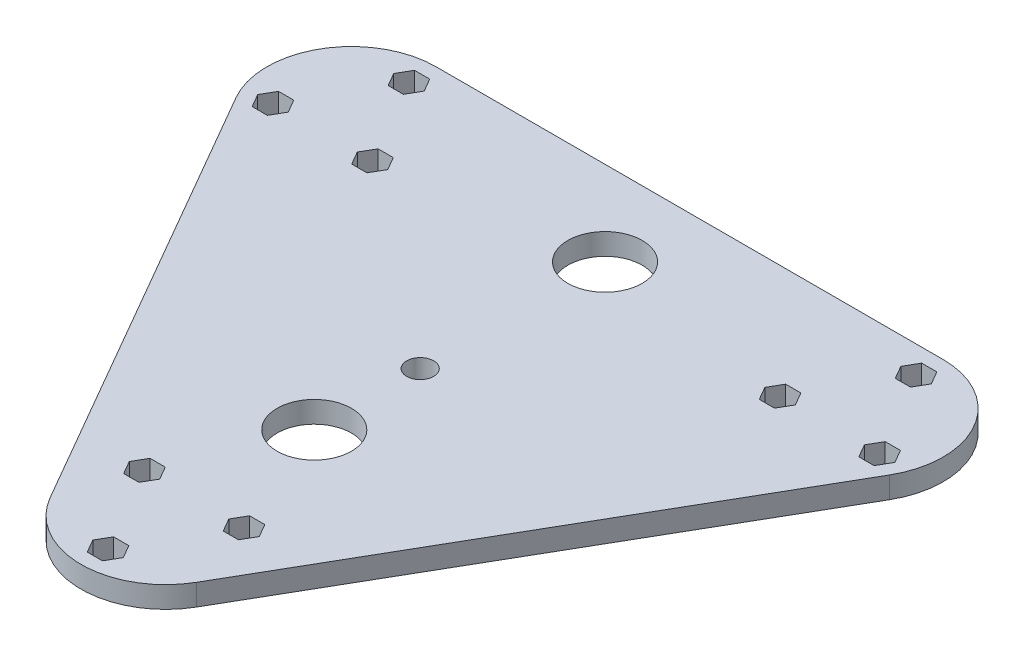
SolidWorks part; units mm, degrees
ref_plane "Plan de face" through (0, 0, 0) normal (0, 0, 1) x (1, 0, 0)
ref_plane "Plan de dessus" through (0, 0, 0) normal (0, 1, 0) x (1, 0, 0)
ref_plane "Plan de droite" through (0, 0, 0) normal (1, 0, 0) x (0, 0, -1)
sketch "Esquisse1" plane through (0, 0, 0) normal (0, 1, 0) x (1, 0, 0)
  line L0 (-96.6546, 52.5069) -> (-21.6546, -77.4931)
  line L1 (96.6546, 52.5069) -> (21.6546, -77.4931)
  line L2 (-75, 90) -> (75, 90)
  line L3 (-75, 65) -> (75, 65) construction
  arc A3 (-75, 90) -> (-96.6546, 52.5069) centre (-75, 65) ccw
  arc A4 (96.6546, 52.5069) -> (75, 90) centre (75, 65) ccw
  arc A5 (-21.6546, -77.4931) -> (21.6546, -77.4931) centre (0, -65) ccw
  circle A6 centre (0, 65) radius 11
  dimension "D1" = 22
  dimension "D6" = 50
  dimension "D2" = 65
  dimension "D3" = 65
  dimension "D4" = 150
  dimension "D5" = 75
extrude "Boss.-Extru.1" add sketch "Esquisse1" along normal blind 6.35
sketch "Esquisse3" plane through (0, 0, 0) normal (0, -1, 0) x (1, 0, 0)
  line L0 (75, -90) -> (-75, -90) construction
  line L1 (-79.5033, -82) -> (-77.2517, -85.9)
  line L2 (-77.2517, -85.9) -> (-72.7483, -85.9)
  line L3 (-72.7483, -85.9) -> (-70.4967, -82)
  line L4 (-70.4967, -82) -> (-72.7483, -78.1)
  line L5 (-72.7483, -78.1) -> (-77.2517, -78.1)
  line L6 (-77.2517, -78.1) -> (-79.5033, -82)
  line L7 (-94.2258, -56.5) -> (-91.9741, -60.4)
  line L8 (-91.9741, -60.4) -> (-87.4708, -60.4)
  line L9 (-87.4708, -60.4) -> (-85.2191, -56.5)
  line L10 (-85.2191, -56.5) -> (-87.4708, -52.6)
  line L11 (-87.4708, -52.6) -> (-91.9741, -52.6)
  line L12 (-91.9741, -52.6) -> (-94.2258, -56.5)
  line L13 (-64.7809, -56.5) -> (-62.5292, -60.4)
  line L14 (-62.5292, -60.4) -> (-58.0259, -60.4)
  line L15 (-58.0259, -60.4) -> (-55.7742, -56.5)
  line L16 (-55.7742, -56.5) -> (-58.0259, -52.6)
  line L17 (-58.0259, -52.6) -> (-62.5292, -52.6)
  line L18 (-62.5292, -52.6) -> (-64.7809, -56.5)
  line L19 (55.7757, -56.4992) -> (58.0274, -60.3992)
  line L20 (58.0274, -60.3992) -> (62.5307, -60.3992)
  line L21 (62.5307, -60.3992) -> (64.7824, -56.4992)
  line L22 (64.7824, -56.4992) -> (62.5307, -52.5992)
  line L23 (62.5307, -52.5992) -> (58.0274, -52.5992)
  line L24 (58.0274, -52.5992) -> (55.7757, -56.4992)
  line L25 (70.4981, -81.9992) -> (72.7498, -85.8992)
  line L26 (72.7498, -85.8992) -> (77.2531, -85.8992)
  line L27 (77.2531, -85.8992) -> (79.5048, -81.9992)
  line L28 (79.5048, -81.9992) -> (77.2531, -78.0992)
  line L29 (77.2531, -78.0992) -> (72.7498, -78.0992)
  line L30 (72.7498, -78.0992) -> (70.4981, -81.9992)
  line L31 (85.2206, -56.4992) -> (87.4722, -60.3992)
  line L32 (87.4722, -60.3992) -> (91.9756, -60.3992)
  line L33 (91.9756, -60.3992) -> (94.2272, -56.4992)
  line L34 (94.2272, -56.4992) -> (91.9756, -52.5992)
  line L35 (91.9756, -52.5992) -> (87.4722, -52.5992)
  line L36 (87.4722, -52.5992) -> (85.2206, -56.4992)
  line L37 (-4.5033, 82) -> (-2.2517, 78.1)
  line L38 (-2.2517, 78.1) -> (2.2517, 78.1)
  line L39 (2.2517, 78.1) -> (4.5033, 82)
  line L40 (4.5033, 82) -> (2.2517, 85.9)
  line L41 (2.2517, 85.9) -> (-2.2517, 85.9)
  line L42 (-2.2517, 85.9) -> (-4.5033, 82)
  line L43 (10.2191, 56.5) -> (12.4708, 52.6)
  line L44 (12.4708, 52.6) -> (16.9741, 52.6)
  line L45 (16.9741, 52.6) -> (19.2258, 56.5)
  line L46 (19.2258, 56.5) -> (16.9741, 60.4)
  line L47 (16.9741, 60.4) -> (12.4708, 60.4)
  line L48 (12.4708, 60.4) -> (10.2191, 56.5)
  line L49 (-19.2258, 56.5) -> (-16.9741, 52.6)
  line L50 (-16.9741, 52.6) -> (-12.4708, 52.6)
  line L51 (-12.4708, 52.6) -> (-10.2191, 56.5)
  line L52 (-10.2191, 56.5) -> (-12.4708, 60.4)
  line L53 (-12.4708, 60.4) -> (-16.9741, 60.4)
  line L54 (-16.9741, 60.4) -> (-19.2258, 56.5)
  circle A0 centre (-75, -82) radius 3.9 construction
  circle A1 centre (-89.7224, -56.5) radius 3.9 construction
  circle A2 centre (-60.2776, -56.5) radius 3.9 construction
  circle A3 centre (60.279, -56.4992) radius 3.9 construction
  circle A4 centre (75.0015, -81.9992) radius 3.9 construction
  circle A5 centre (89.7239, -56.4992) radius 3.9 construction
  circle A6 centre (0, 82) radius 3.9 construction
  circle A7 centre (14.7224, 56.5) radius 3.9 construction
  circle A8 centre (-14.7224, 56.5) radius 3.9 construction
  dimension "D1" = 7.8
extrude "Enlèv. mat.-Extru.1" cut sketch "Esquisse3" against normal through all
sketch "Esquisse4" plane through (0, 6.35, 0) normal (0, 1, 0) x (1, 0, 0)
  circle A0 centre (0.0008, 10.325) radius 4
  circle A5 centre (0.0008, 10.325) radius 4 construction
  point P5 (0, 9.9237)
  dimension "D1" = 8
extrude "Enlèv. mat.-Extru.2" cut sketch "Esquisse4" against normal through all
sketch "Esquisse5" plane through (0, 6.35, 0) normal (0, 1, 0) x (1, 0, 0)
  circle A0 centre (0, -21) radius 11
  circle A1 centre (0, 65) radius 5.7 construction
  circle A2 centre (0, 65) radius 11 construction
  dimension "D1" = 86
extrude "Enlèv. mat.-Extru.3" cut sketch "Esquisse5" against normal through all
equation "\"diam_long_rod\"=8"
equation "\"D1@Esquisse4\"=\"diam_long_rod\""
